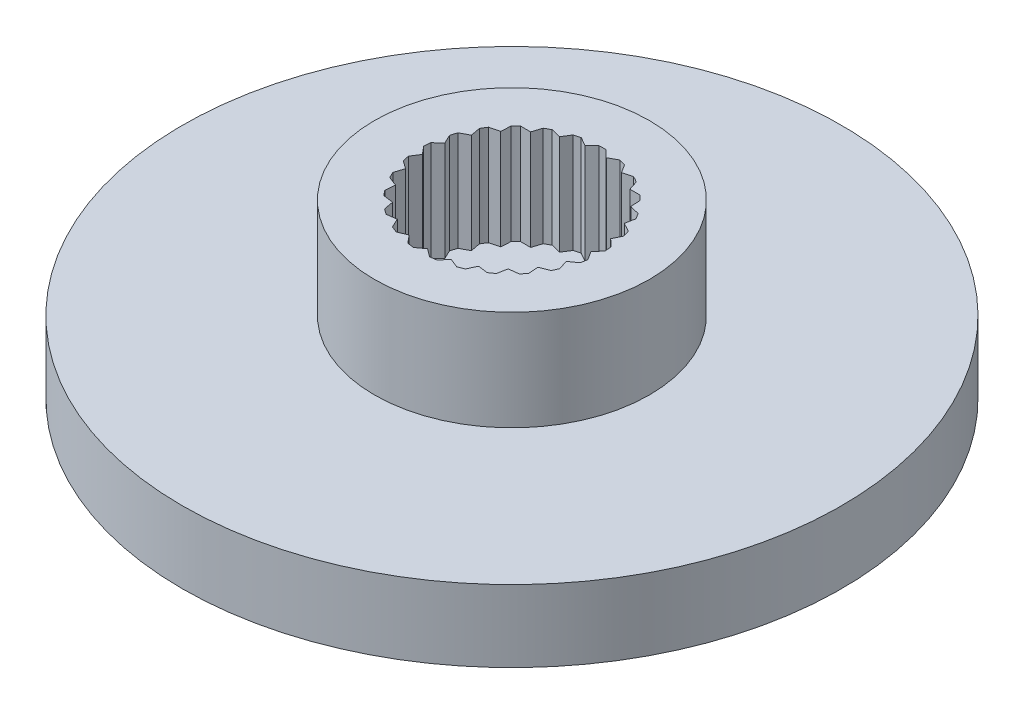
SolidWorks part; units mm, degrees
material "ABS"
ref_plane "Front Plane" through (0, 0, 0) normal (0, 0, 1) x (1, 0, 0)
ref_plane "Top Plane" through (0, 0, 0) normal (0, 1, 0) x (1, 0, 0)
ref_plane "Right Plane" through (0, 0, 0) normal (1, 0, 0) x (0, 0, -1)
sketch "Sketch2" plane through (0, 0, 0) normal (0, 1, 0) x (1, 0, 0)
  circle A0 centre (0, 0) radius 6
  circle A1 centre (0, 0) radius 1.5
  dimension "D1" = 12
  dimension "D2" = 3
extrude "Boss-Extrude1" add sketch "Sketch2" along normal mid plane 2.3
sketch "Sketch3" plane through (0, 1.15, 0) normal (0, 1, 0) x (1, 0, 0)
  line L0 (0, 0) -> (0, 2.9) construction
  line L3 (0, 0) -> (0.376, 2.9763) construction
  line L52 (0.1074, 2.898) -> (0.3384, 2.6787)
  line L53 (-0.1074, 2.898) -> (-0.3384, 2.6787)
  line L54 (0.8248, 2.7802) -> (0.9939, 2.5104)
  line L55 (0.6167, 2.8337) -> (0.3384, 2.6787)
  line L56 (1.4903, 2.4878) -> (1.587, 2.1843)
  line L57 (1.302, 2.5913) -> (0.9939, 2.5104)
  line L58 (2.0621, 2.039) -> (2.0804, 1.721)
  line L59 (1.9055, 2.1861) -> (1.587, 2.1843)
  line L60 (2.5044, 1.4621) -> (2.443, 1.1496)
  line L61 (2.3893, 1.6435) -> (2.0804, 1.721)
  line L62 (2.7894, 0.7934) -> (2.6522, 0.5059)
  line L63 (2.723, 0.9977) -> (2.443, 1.1496)
  line L64 (2.899, 0.0748) -> (2.6947, -0.1695)
  line L65 (2.8855, 0.2892) -> (2.6522, 0.5059)
  line L66 (2.8265, -0.6486) -> (2.5679, -0.8343)
  line L67 (2.8668, -0.4375) -> (2.6947, -0.1695)
  line L68 (2.5765, -1.3311) -> (2.2797, -1.4467)
  line L69 (2.6679, -1.1367) -> (2.5679, -0.8343)
  line L70 (2.1645, -1.93) -> (1.8483, -1.9682)
  line L71 (2.3014, -1.7645) -> (2.2797, -1.4467)
  line L72 (1.6165, -2.4077) -> (1.3007, -2.366)
  line L73 (1.7903, -2.2814) -> (1.8483, -1.9682)
  line L74 (0.967, -2.734) -> (0.6715, -2.6152)
  line L75 (1.1667, -2.655) -> (1.3007, -2.366)
  line L76 (0.2566, -2.8886) -> (0, -2.7)
  line L77 (0.4698, -2.8617) -> (0.6715, -2.6152)
  line L78 (-0.4698, -2.8617) -> (-0.6715, -2.6152)
  line L79 (-0.2566, -2.8886) -> (0, -2.7)
  line L80 (-1.1667, -2.655) -> (-1.3007, -2.366)
  line L81 (-0.967, -2.734) -> (-0.6715, -2.6152)
  line L82 (-1.7903, -2.2814) -> (-1.8483, -1.9682)
  line L83 (-1.6165, -2.4077) -> (-1.3007, -2.366)
  line L84 (-2.3014, -1.7645) -> (-2.2797, -1.4467)
  line L85 (-2.1645, -1.93) -> (-1.8483, -1.9682)
  line L86 (-2.6679, -1.1367) -> (-2.5679, -0.8343)
  line L87 (-2.5765, -1.3311) -> (-2.2797, -1.4467)
  line L88 (-2.8668, -0.4375) -> (-2.6947, -0.1695)
  line L89 (-2.8265, -0.6486) -> (-2.5679, -0.8343)
  line L90 (-2.8855, 0.2892) -> (-2.6522, 0.5059)
  line L91 (-2.899, 0.0748) -> (-2.6947, -0.1695)
  line L92 (-2.723, 0.9977) -> (-2.443, 1.1496)
  line L93 (-2.7894, 0.7934) -> (-2.6522, 0.5059)
  line L94 (-2.3893, 1.6435) -> (-2.0804, 1.721)
  line L95 (-2.5044, 1.4621) -> (-2.443, 1.1496)
  line L96 (-1.9055, 2.1861) -> (-1.587, 2.1843)
  line L97 (-2.0621, 2.039) -> (-2.0804, 1.721)
  line L98 (-1.302, 2.5913) -> (-0.9939, 2.5104)
  line L99 (-1.4903, 2.4878) -> (-1.587, 2.1843)
  line L100 (-0.6167, 2.8337) -> (-0.3384, 2.6787)
  line L101 (-0.8248, 2.7802) -> (-0.9939, 2.5104)
  line L102 (-2.533, 1.6075) -> (-2.3893, 1.6435) construction
  line L103 (-2.533, 1.6075) -> (-2.5044, 1.4621) construction
  line L104 (-2.8532, 0.9271) -> (-2.723, 0.9977) construction
  line L105 (-2.8532, 0.9271) -> (-2.7894, 0.7934) construction
  line L106 (-2.9941, 0.1884) -> (-2.8855, 0.2892) construction
  line L107 (-2.9941, 0.1884) -> (-2.899, 0.0748) construction
  line L108 (-2.9469, -0.5621) -> (-2.8668, -0.4375) construction
  line L109 (-2.9469, -0.5621) -> (-2.8265, -0.6486) construction
  line L110 (0, 3) -> (0.1074, 2.898) construction
  line L111 (0, 2.9) -> (0, 3) construction
  line L112 (0, 3) -> (-0.1074, 2.898) construction
  line L113 (-0.7461, 2.9057) -> (-0.6167, 2.8337) construction
  line L114 (-0.7461, 2.9057) -> (-0.8248, 2.7802) construction
  line L115 (-1.4453, 2.6289) -> (-1.302, 2.5913) construction
  line L116 (-1.4453, 2.6289) -> (-1.4903, 2.4878) construction
  line L117 (-2.0536, 2.1869) -> (-1.9055, 2.1861) construction
  line L118 (-2.0536, 2.1869) -> (-2.0621, 2.039) construction
  line L119 (-2.7145, -1.2773) -> (-2.6679, -1.1367) construction
  line L120 (-2.7145, -1.2773) -> (-2.5765, -1.3311) construction
  line L121 (-2.3115, -1.9123) -> (-2.3014, -1.7645) construction
  line L122 (-2.3115, -1.9123) -> (-2.1645, -1.93) construction
  line L123 (-1.7634, -2.4271) -> (-1.7903, -2.2814) construction
  line L124 (-1.7634, -2.4271) -> (-1.6165, -2.4077) construction
  line L125 (-1.1044, -2.7893) -> (-1.1667, -2.655) construction
  line L126 (-1.1044, -2.7893) -> (-0.967, -2.734) construction
  line L127 (-0.376, -2.9763) -> (-0.4698, -2.8617) construction
  line L128 (-0.376, -2.9763) -> (-0.2566, -2.8886) construction
  line L129 (0.376, -2.9763) -> (0.2566, -2.8886) construction
  line L130 (0.376, -2.9763) -> (0.4698, -2.8617) construction
  line L131 (1.1044, -2.7893) -> (0.967, -2.734) construction
  line L132 (1.1044, -2.7893) -> (1.1667, -2.655) construction
  line L133 (1.7634, -2.4271) -> (1.6165, -2.4077) construction
  line L134 (1.7634, -2.4271) -> (1.7903, -2.2814) construction
  line L135 (2.3115, -1.9123) -> (2.3014, -1.7645) construction
  line L136 (2.3115, -1.9123) -> (2.1645, -1.93) construction
  line L137 (2.7145, -1.2773) -> (2.6679, -1.1367) construction
  line L138 (2.7145, -1.2773) -> (2.5765, -1.3311) construction
  line L139 (2.9469, -0.5621) -> (2.8668, -0.4375) construction
  line L140 (2.9469, -0.5621) -> (2.8265, -0.6486) construction
  line L141 (2.9941, 0.1884) -> (2.8855, 0.2892) construction
  line L142 (2.9941, 0.1884) -> (2.899, 0.0748) construction
  line L143 (2.8532, 0.9271) -> (2.723, 0.9977) construction
  line L144 (2.8532, 0.9271) -> (2.7894, 0.7934) construction
  line L145 (2.533, 1.6075) -> (2.3893, 1.6435) construction
  line L146 (2.533, 1.6075) -> (2.5044, 1.4621) construction
  line L147 (2.0536, 2.1869) -> (1.9055, 2.1861) construction
  line L148 (2.0536, 2.1869) -> (2.0621, 2.039) construction
  line L149 (1.4453, 2.6289) -> (1.302, 2.5913) construction
  line L150 (1.4453, 2.6289) -> (1.4903, 2.4878) construction
  line L151 (0.7461, 2.9057) -> (0.6167, 2.8337) construction
  line L152 (0.7461, 2.9057) -> (0.8248, 2.7802) construction
  circle A0 centre (0, 0) radius 4.4
  circle A1 centre (0, 0) radius 3 construction
  circle A2 centre (0, 0) radius 2.7 construction
  arc A3 (-0.6167, 2.8337) -> (-0.8248, 2.7802) centre (0, 0) ccw
  arc A4 (-0.1074, 2.898) -> (-0.6167, 2.8337) centre (0, 0) ccw construction
  arc A5 (-0.8248, 2.7802) -> (-1.302, 2.5913) centre (0, 0) ccw construction
  arc A6 (-1.302, 2.5913) -> (-1.4903, 2.4878) centre (0, 0) ccw
  arc A7 (-1.4903, 2.4878) -> (-1.9055, 2.1861) centre (0, 0) ccw construction
  arc A8 (-1.9055, 2.1861) -> (-2.0621, 2.039) centre (0, 0) ccw
  arc A9 (-2.0621, 2.039) -> (-2.3893, 1.6435) centre (0, 0) ccw construction
  arc A10 (-2.3893, 1.6435) -> (-2.5044, 1.4621) centre (0, 0) ccw
  arc A11 (-2.5044, 1.4621) -> (-2.723, 0.9977) centre (0, 0) ccw construction
  arc A12 (-2.723, 0.9977) -> (-2.7894, 0.7934) centre (0, 0) ccw
  arc A13 (-2.7894, 0.7934) -> (-2.8855, 0.2892) centre (0, 0) ccw construction
  arc A14 (-2.8855, 0.2892) -> (-2.899, 0.0748) centre (0, 0) ccw
  arc A15 (-2.899, 0.0748) -> (-2.8668, -0.4375) centre (0, 0) ccw construction
  arc A16 (-2.8668, -0.4375) -> (-2.8265, -0.6486) centre (0, 0) ccw
  arc A17 (-2.8265, -0.6486) -> (-2.6679, -1.1367) centre (0, 0) ccw construction
  arc A18 (-2.6679, -1.1367) -> (-2.5765, -1.3311) centre (0, 0) ccw
  arc A19 (-2.5765, -1.3311) -> (-2.3014, -1.7645) centre (0, 0) ccw construction
  arc A20 (-2.3014, -1.7645) -> (-2.1645, -1.93) centre (0, 0) ccw
  arc A21 (-2.1645, -1.93) -> (-1.7903, -2.2814) centre (0, 0) ccw construction
  arc A22 (-1.7903, -2.2814) -> (-1.6165, -2.4077) centre (0, 0) ccw
  arc A23 (-1.6165, -2.4077) -> (-1.1667, -2.655) centre (0, 0) ccw construction
  arc A24 (-1.1667, -2.655) -> (-0.967, -2.734) centre (0, 0) ccw
  arc A25 (-0.967, -2.734) -> (-0.4698, -2.8617) centre (0, 0) ccw construction
  arc A26 (-0.4698, -2.8617) -> (-0.2566, -2.8886) centre (0, 0) ccw
  arc A27 (-0.2566, -2.8886) -> (0.2566, -2.8886) centre (0, 0) ccw construction
  arc A28 (0.2566, -2.8886) -> (0.4698, -2.8617) centre (0, 0) ccw
  arc A29 (0.4698, -2.8617) -> (0.967, -2.734) centre (0, 0) ccw construction
  arc A30 (0.967, -2.734) -> (1.1667, -2.655) centre (0, 0) ccw
  arc A31 (1.1667, -2.655) -> (1.6165, -2.4077) centre (0, 0) ccw construction
  arc A32 (1.6165, -2.4077) -> (1.7903, -2.2814) centre (0, 0) ccw
  arc A33 (1.7903, -2.2814) -> (2.1645, -1.93) centre (0, 0) ccw construction
  arc A34 (2.1645, -1.93) -> (2.3014, -1.7645) centre (0, 0) ccw
  arc A35 (2.3014, -1.7645) -> (2.5765, -1.3311) centre (0, 0) ccw construction
  arc A36 (2.5765, -1.3311) -> (2.6679, -1.1367) centre (0, 0) ccw
  arc A37 (2.6679, -1.1367) -> (2.8265, -0.6486) centre (0, 0) ccw construction
  arc A38 (2.8265, -0.6486) -> (2.8668, -0.4375) centre (0, 0) ccw
  arc A39 (2.8668, -0.4375) -> (2.899, 0.0748) centre (0, 0) ccw construction
  arc A40 (2.899, 0.0748) -> (2.8855, 0.2892) centre (0, 0) ccw
  arc A41 (2.8855, 0.2892) -> (2.7894, 0.7934) centre (0, 0) ccw construction
  arc A42 (2.7894, 0.7934) -> (2.723, 0.9977) centre (0, 0) ccw
  arc A43 (2.723, 0.9977) -> (2.5044, 1.4621) centre (0, 0) ccw construction
  arc A44 (2.5044, 1.4621) -> (2.3893, 1.6435) centre (0, 0) ccw
  arc A45 (2.3893, 1.6435) -> (2.0621, 2.039) centre (0, 0) ccw construction
  arc A46 (2.0621, 2.039) -> (1.9055, 2.1861) centre (0, 0) ccw
  arc A47 (1.9055, 2.1861) -> (1.4903, 2.4878) centre (0, 0) ccw construction
  arc A48 (1.4903, 2.4878) -> (1.302, 2.5913) centre (0, 0) ccw
  arc A49 (1.302, 2.5913) -> (0.8248, 2.7802) centre (0, 0) ccw construction
  arc A50 (0.8248, 2.7802) -> (0.6167, 2.8337) centre (0, 0) ccw
  arc A51 (0.3635, 2.8771) -> (0.1074, 2.898) centre (0, 0) ccw construction
  arc A52 (0.1074, 2.898) -> (-0.1074, 2.898) centre (0, 0) ccw
  arc A53 (0.6167, 2.8337) -> (0.3635, 2.8771) centre (0, 0) ccw construction
  point P84 (0, 0)
  dimension "D1" = 8.8
  dimension "D2" = 5.4
  dimension "D3" = 6
  dimension "D6" = 5.8
  dimension "D4" = 7.2
  dimension "D5" = 25
extrude "Boss-Extrude2" add sketch "Sketch3" along normal blind 3.2
sketch "Sketch4" plane through (0, 0, 0) normal (0, 1, 0) x (1, 0, 0)
  line L0 (0, 0) -> (13, 0) construction
  line L1 (3.9686, 4.5) -> (14.0007, 2.4494)
  line L2 (3.9686, -4.5) -> (14.0007, -2.4494)
  line L3 (13, 0) -> (10, 0) construction
  circle A0 centre (0, 0) radius 6 construction
  arc A1 (3.9686, -4.5) -> (3.9686, 4.5) centre (0, 0) ccw
  arc A2 (14.0007, 2.4494) -> (14.0007, -2.4494) centre (13.5, 0) cw
  circle A3 centre (13, 0) radius 0.75
  circle A4 centre (10, 0) radius 0.75
  circle A5 centre (7, 0) radius 0.75
  dimension "D3" = 2.5
  dimension "D5" = 1.5
  dimension "D2" = 9
  dimension "D7" = 3
  dimension "D4" = 0.5
  dimension "D1" = 13
  dimension "D6" = 3
extrude "Boss-Extrude3" [suppressed] add sketch "Sketch4" along normal mid plane 2.3
pattern_circular "CirPattern1" [suppressed] count 6 over 360
sketch "Sketch5" plane through (0, 0, 0) normal (0, 1, 0) x (1, 0, 0)
  circle A0 centre (0, 0) radius 10.541
  circle A13 centre (0, 0) radius 1.5 construction
  circle A14 centre (0, 0) radius 1.5
  point P8 (0, 7)
  point P31 (0, 0)
  dimension "D1" = 21.082
extrude "Boss-Extrude4" add sketch "Sketch5" along normal mid plane 2.3
sketch "Sketch8" plane through (0, -1.15, 0) normal (0, 1, 0) x (1, 0, 0)
  line L0 (0, 0) -> (0, 9.7484) construction
  arc A0 (0.31, 7.4936) -> (-0.31, 7.4936) centre (0, 0) ccw
  circle A1 centre (0, 0) radius 5.5
  arc A2 (-1.04, 5.4008) -> (-0.31, 7.4936) centre (4.3152, 4.7065) cw
  arc A3 (1.04, 5.4008) -> (0.31, 7.4936) centre (-4.3152, 4.7065) ccw
  arc A4 (3.4307, 4.2988) -> (3.7569, 6.4912) centre (-1.6337, 6.1728) ccw
  arc A5 (1.589, 5.2655) -> (3.208, 6.7793) centre (6.0081, 2.1621) cw
  circle A6 centre (0, 0) radius 10.541 construction
  arc A7 (3.7569, 6.4912) -> (3.208, 6.7793) centre (0, 0) ccw
  arc A8 (5.0355, 2.2121) -> (6.3432, 4.0017) centre (1.4221, 6.225) ccw
  arc A10 (3.854, 3.9239) -> (5.991, 4.512) centre (6.3247, -0.8777) cw
  arc A11 (6.3432, 4.0017) -> (5.991, 4.512) centre (0, 0) ccw
  arc A13 (5.4868, -0.3814) -> (7.4763, 0.5955) centre (4.1521, 4.851) ccw
  arc A14 (5.236, 1.6834) -> (7.4016, 1.211) centre (5.1924, -3.7164) cw
  arc A16 (7.4763, 0.5955) -> (7.4016, 1.211) centre (0, 0) ccw
  arc A17 (4.681, -2.8876) -> (6.8967, -2.9471) centre (5.9309, 2.3658) ccw
  arc A19 (5.4186, -0.9427) -> (7.1166, -2.3674) centre (2.8705, -5.7037) cw
  arc A20 (6.8967, -2.9471) -> (7.1166, -2.3674) centre (0, 0) ccw
  arc A22 (2.8029, -4.7322) -> (4.7371, -5.8146) centre (6.351, -0.6614) ccw
  arc A23 (4.3598, -3.3529) -> (5.2012, -5.4035) centre (-0.1089, -6.3844) cw
  arc A25 (4.7371, -5.8146) -> (5.2012, -5.4035) centre (0, 0) ccw
  arc A26 (0.2827, -5.4927) -> (1.4923, -7.35) centre (5.3161, -3.5371) ccw
  arc A28 (2.3023, -4.995) -> (2.0943, -7.2017) centre (-3.0634, -5.6025) cw
  arc A29 (1.4923, -7.35) -> (2.0943, -7.2017) centre (0, 0) ccw
  arc A31 (-2.3023, -4.995) -> (-2.0943, -7.2017) centre (3.0634, -5.6025) ccw
  arc A32 (-0.2827, -5.4927) -> (-1.4923, -7.35) centre (-5.3161, -3.5371) cw
  arc A34 (-2.0943, -7.2017) -> (-1.4923, -7.35) centre (0, 0) ccw
  arc A35 (-4.3598, -3.3529) -> (-5.2012, -5.4035) centre (0.1089, -6.3844) ccw
  arc A59 (-2.8029, -4.7322) -> (-4.7371, -5.8146) centre (-6.351, -0.6614) cw
  arc A60 (-5.2012, -5.4035) -> (-4.7371, -5.8146) centre (0, 0) ccw
  arc A61 (-5.4186, -0.9427) -> (-7.1166, -2.3674) centre (-2.8705, -5.7037) ccw
  arc A62 (-4.681, -2.8876) -> (-6.8967, -2.9471) centre (-5.9309, 2.3658) cw
  arc A63 (-7.1166, -2.3674) -> (-6.8967, -2.9471) centre (0, 0) ccw
  arc A64 (-5.236, 1.6834) -> (-7.4016, 1.211) centre (-5.1924, -3.7164) ccw
  arc A65 (-5.4868, -0.3814) -> (-7.4763, 0.5955) centre (-4.1521, 4.851) cw
  arc A66 (-7.4016, 1.211) -> (-7.4763, 0.5955) centre (0, 0) ccw
  arc A67 (-3.854, 3.9239) -> (-5.991, 4.512) centre (-6.3247, -0.8777) ccw
  arc A68 (-5.0355, 2.2121) -> (-6.3432, 4.0017) centre (-1.4221, 6.225) cw
  arc A69 (-5.991, 4.512) -> (-6.3432, 4.0017) centre (0, 0) ccw
  arc A70 (-1.589, 5.2655) -> (-3.208, 6.7793) centre (-6.0081, 2.1621) ccw
  arc A71 (-3.4307, 4.2988) -> (-3.7569, 6.4912) centre (1.6337, 6.1728) cw
  arc A72 (-3.208, 6.7793) -> (-3.7569, 6.4912) centre (0, 0) ccw
  point P79 (0, 0)
  point P174 (0, 0)
  dimension "D1" = 15
  dimension "D2" = 11
  dimension "D5" = 5.4
  dimension "D3" = 0.62
  dimension "D4" = 2.08
  dimension "D7" = 13
extrude "Cut-Extrude1" cut sketch "Sketch8" along direction (0, 1, 0) on the side of the normal blind 1
equation "\"N_hole\"= 3"
equation "\"N_horn\"= 6"
equation "\"D6@Sketch4\"=\"N_hole\""
equation "\"D1@CirPattern1\"=\"N_horn\""
equation "\"D1@Sketch4\"=(\"N_hole\" - 1) *3 +7"
